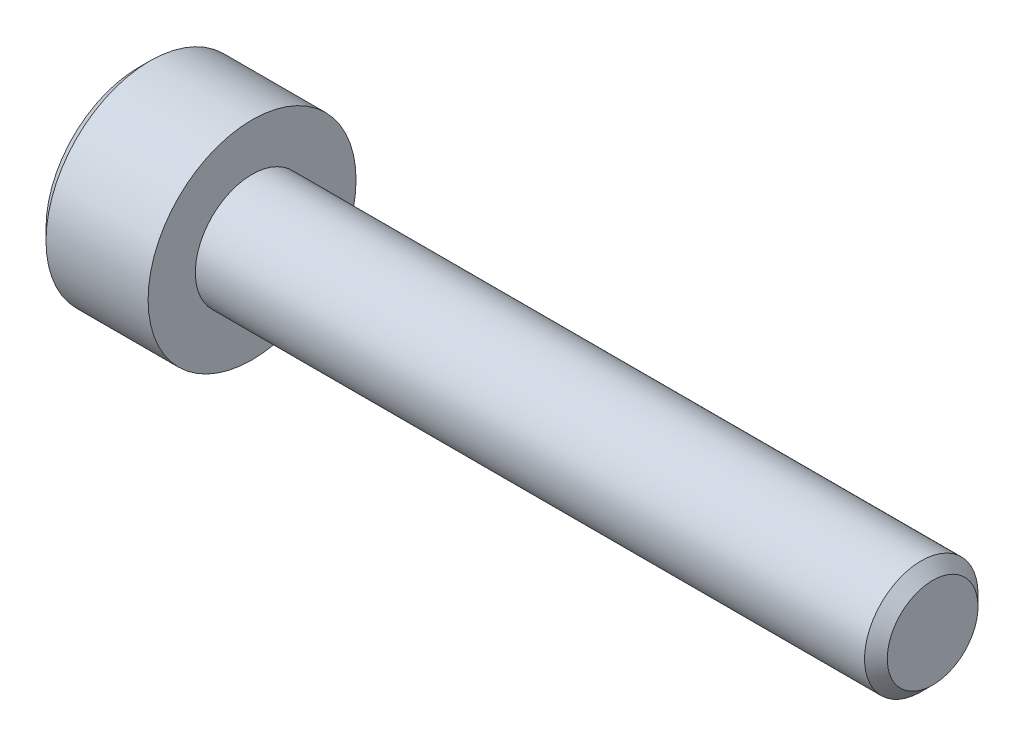
SolidWorks part; units mm, degrees
ref_plane "Front Plane" through (0, 0, 0) normal (0, 0, 1) x (1, 0, 0)
ref_plane "Top Plane" through (0, 0, 0) normal (0, 1, 0) x (1, 0, 0)
ref_plane "Right Plane" through (0, 0, 0) normal (1, 0, 0) x (0, 0, -1)
sketch "Sketch1" plane through (0, 0, 0) normal (0, 0, 1) x (1, 0, 0)
  line L0 (-3, 2.75) -> (-3, 0)
  line L1 (-3, 0) -> (0, 0)
  line L2 (0, 0) -> (0, 2.75)
  line L3 (0, 2.75) -> (-3, 2.75)
  line L4 (-3, 0) -> (0, 0) construction
revolve "Revolve1" add sketch "Sketch1" angle 360 about L4
sketch "Sketch2" plane through (0, 0, 0) normal (1, 0, 0) x (0, 0, -1)
  circle A0 centre (0, 0) radius 1.5
extrude "Boss-Extrude1" add sketch "Sketch2" along normal blind 18
sketch "Sketch3" plane through (-3, 0, 0) normal (-1, 0, 0) x (0, 0, 1)
  line L0 (1.25, -0.7217) -> (1.25, 0.7217)
  line L1 (1.25, 0.7217) -> (0, 1.4434)
  line L2 (0, 1.4434) -> (-1.25, 0.7217)
  line L3 (-1.25, 0.7217) -> (-1.25, -0.7217)
  line L4 (-1.25, -0.7217) -> (0, -1.4434)
  line L5 (0, -1.4434) -> (1.25, -0.7217)
extrude "Cut-Extrude1" cut sketch "Sketch3" against normal blind 1.5
sketch "Sketch4" plane through (0, 0, 0) normal (0, 0, 1) x (1, 0, 0)
  line L0 (-1.5, 1.25) -> (-1.5, 0)
  line L1 (-1.5, 0) -> (-1.1651, 0)
  line L2 (-1.1651, 0) -> (-1.5, 1.25)
  line L3 (-1.5, 0) -> (-1.165, 0) construction
revolve "Cut-Revolve1" cut sketch "Sketch4" angle 360 about L3
chamfer "Chamfer1" distance 0.3 angle 45 2 edges at (18, 0, -1.5) (-3, 0, -2.75)
